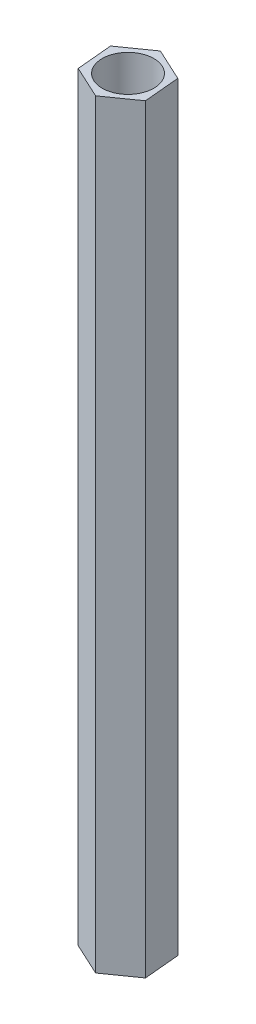
SolidWorks part; units mm, degrees
ref_plane "前视基准面" through (0, 0, 0) normal (0, 0, 1) x (1, 0, 0)
ref_plane "上视基准面" through (0, 0, 0) normal (0, 1, 0) x (1, 0, 0)
ref_plane "右视基准面" through (0, 0, 0) normal (1, 0, 0) x (0, 0, -1)
sketch "草图1" plane through (0, 0, 0) normal (0, 1, 0) x (1, 0, 0)
  line L1 (1.5724, -0.7264) -> (1.4153, 0.9985)
  line L2 (1.4153, 0.9985) -> (-0.1571, 1.7249)
  line L3 (-0.1571, 1.7249) -> (-1.5724, 0.7264)
  line L4 (-1.5724, 0.7264) -> (-1.4153, -0.9985)
  line L5 (-1.4153, -0.9985) -> (0.1571, -1.7249)
  line L6 (0.1571, -1.7249) -> (1.5724, -0.7264)
  circle A0 centre (0, 0) radius 1.5 construction
  dimension "D1" = 3
extrude "凸台-拉伸1" add sketch "草图1" along normal blind 36.82
sketch "草图2" plane through (0, 36.82, 0) normal (0, 1, 0) x (1, 0, 0)
  circle A0 centre (0, 0) radius 1.25
  dimension "D1" = 2.5
extrude "切除-拉伸1" cut sketch "草图2" against normal through all
